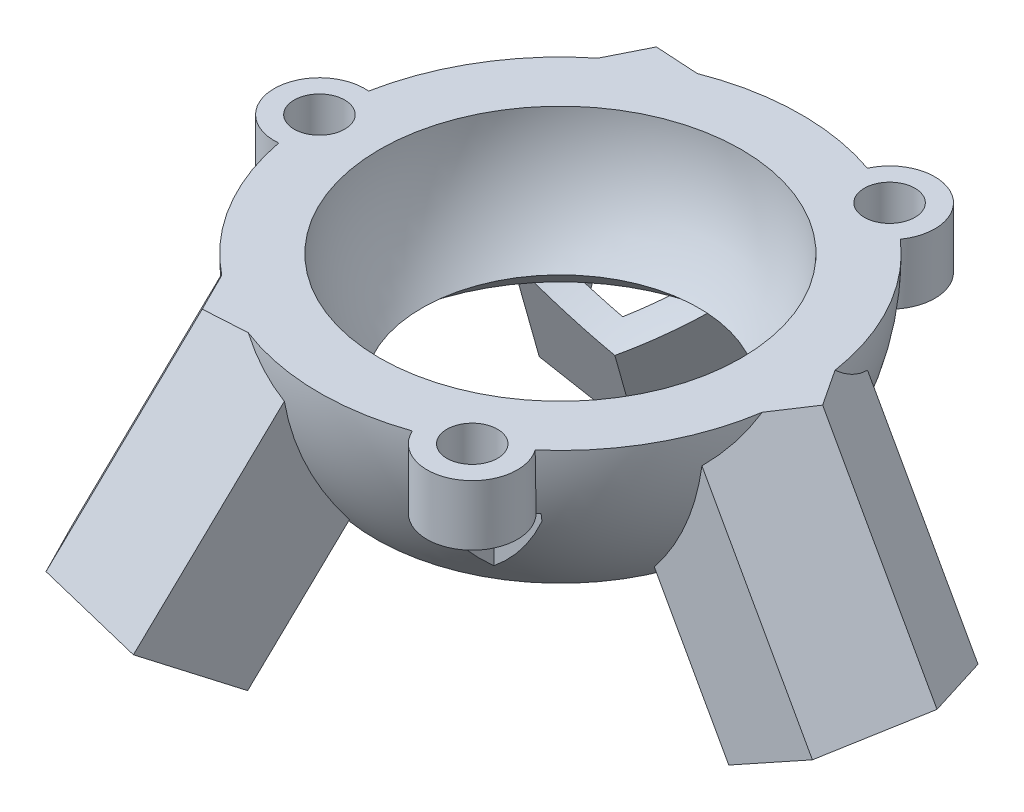
SolidWorks part; units mm, degrees
ref_plane "Ön Düzlem" through (0, 0, 0) normal (0, 0, 1) x (1, 0, 0)
ref_plane "Üst Düzlem" through (0, 0, 0) normal (0, 1, 0) x (1, 0, 0)
ref_plane "Sağ Düzlem" through (0, 0, 0) normal (1, 0, 0) x (0, 0, -1)
sketch "Çizim3" plane through (0, 0, 0) normal (0, 0, 1) x (1, 0, 0)
  line L0 (0, 24.312) -> (0, -34.2324) construction
  line L2 (-11.4907, -9.6418) -> (-15.3209, -12.8558)
  line L3 (-20, 0) -> (-15, 0)
  arc A0 (-15, 0) -> (-11.4907, -9.6418) centre (0, 0) ccw
  arc A1 (-20, 0) -> (-15.3209, -12.8558) centre (0, 0) ccw
  point P9 (0, 0)
  dimension "D1" = 30
  dimension "D2" = 5
revolve "Döndür1" add sketch "Çizim3" angle 360 about L0
sketch "Çizim4" plane through (0, 0, 0) normal (0, 1, 0) x (1, 0, 0)
  line L0 (0, 0) -> (-53.8435, 0) construction
  line L1 (0, 0) -> (20, 34.641) construction
  line L2 (0, 0) -> (20, -34.641) construction
  line L3 (10, 17.3205) -> (-20, 0) construction
  line L4 (-20, 0) -> (10, -17.3205) construction
  line L5 (10, -17.3205) -> (10, 17.3205) construction
  circle A0 centre (10, 17.3205) radius 1.75
  circle A1 centre (10, -17.3205) radius 1.75
  circle A2 centre (-20, 0) radius 1.75
  circle A3 centre (0, 0) radius 20 construction
  circle A4 centre (10, 17.3205) radius 3.75
  circle A5 centre (-20, 0) radius 3.75
  circle A6 centre (10, -17.3205) radius 3.75
  dimension "D3" = 3.5
  dimension "D4" = 2
  dimension "D1" = 120
  dimension "D2" = 120
extrude "Yükseklik-Ekstrüzyon1" add sketch "Çizim4" against normal blind 5
sketch "Çizim5" plane through (0, 0, 0) normal (0, 1, 0) x (1, 0, 0)
  circle A0 centre (10, 17.3205) radius 2.1
  circle A1 centre (-20, 0) radius 2.1
  arc A2 (-19.9234, 1.7483) -> (-19.9234, -1.7483) centre (0, 0) ccw construction
  circle A3 centre (10, -17.3205) radius 2.1
  arc A4 (8.4476, -18.1284) -> (11.4758, -16.38) centre (0, 0) ccw construction
  dimension "D1" = 4.2
extrude "Kes-Ekstrüzyon1" cut sketch "Çizim5" against normal blind 24
ref_plane "Düzlem1" through (0, -41.1703, 0) normal (0, 1, 0) x (1, 0, 0)
sketch "Çizim6" plane through (0, -41.1703, 0) normal (0, 1, 0) x (1, 0, 0)
  line L0 (0, 0) -> (10.7692, 17.7646) construction
  line L1 (0, 0) -> (-20, 0) construction
  line L2 (0, 0) -> (10.7692, -17.7646) construction
  line L4 (-16, 0) -> (-18, 3.4641)
  line L5 (-18, 3.4641) -> (-22, 3.4641)
  line L6 (-22, 3.4641) -> (-24, 0)
  line L7 (-24, 0) -> (-22, -3.4641)
  line L8 (-22, -3.4641) -> (-18, -3.4641)
  line L9 (-18, -3.4641) -> (-16, 0)
  line L10 (8.7692, 14.3005) -> (12.7692, 14.3005)
  line L11 (12.7692, 14.3005) -> (14.7692, 17.7646)
  line L12 (14.7692, 17.7646) -> (12.7692, 21.2287)
  line L13 (12.7692, 21.2287) -> (8.7692, 21.2287)
  line L14 (8.7692, 21.2287) -> (6.7692, 17.7646)
  line L15 (6.7692, 17.7646) -> (8.7692, 14.3005)
  line L16 (8.7692, -14.3005) -> (6.7692, -17.7646)
  line L17 (6.7692, -17.7646) -> (8.7692, -21.2287)
  line L18 (8.7692, -21.2287) -> (12.7692, -21.2287)
  line L19 (12.7692, -21.2287) -> (14.7692, -17.7646)
  line L20 (14.7692, -17.7646) -> (12.7692, -14.3005)
  line L21 (12.7692, -14.3005) -> (8.7692, -14.3005)
  circle A0 centre (-20, 0) radius 3.4641 construction
  circle A1 centre (10.7692, 17.7646) radius 3.4641 construction
  circle A2 centre (10.7692, -17.7646) radius 3.4641 construction
  dimension "D1" = 8
extrude "Kes-Ekstrüzyon2" cut sketch "Çizim6" along normal up to surface (36.1703 mm away) up to face at (10.5217, -5, 18.2242)
sketch "Çizim7" plane through (0, 0, 0) normal (0, 1, 0) x (1, 0, 0)
  line L0 (0, 0) -> (-10, -17.3205) construction
  line L1 (0, 0) -> (20, 0) construction
  line L2 (0, 0) -> (-10, 17.3205) construction
  arc A0 (-19.6484, -3.7335) -> (6.5909, -18.8828) centre (0, 0) ccw construction
  arc A1 (13.0575, -15.1493) -> (13.0575, 15.1493) centre (0, 0) ccw construction
  arc A2 (6.5909, 18.8828) -> (-19.6484, 3.7335) centre (0, 0) ccw construction
sketch "Çizim8" plane through (0, 0, 0) normal (0, 0, 1) x (1, 0, 0)
  line L0 (0, 67.9516) -> (0, -85.0049) construction
sketch3d "3B Çizim2"
  line L0 (0, 22.8931, 0) -> (26.7388, -25.3451, 0) construction
  line L3 (0, 67.9516, 0) -> (0, -85.0049, 0) construction
  dimension "D1" = 29
ref_plane "Düzlem2" through (26.7388, -25.3451, 0) normal (0.4848, -0.8746, 0) x (-0.8746, -0.4848, 0)
sketch "Çizim9" plane through (26.7388, -25.3451, 0) normal (0.4848, -0.8746, 0) x (-0.8746, -0.4848, 0)
  line L0 (3.9672, 6.8714) -> (-3.9672, 6.8714)
  line L1 (5.625, 0) -> (2.8125, 4.8714)
  line L2 (2.8125, 4.8714) -> (-2.8125, 4.8714)
  line L3 (-2.8125, 4.8714) -> (-5.625, 0)
  line L4 (-5.625, 0) -> (-2.8125, -4.8714)
  line L5 (-2.8125, -4.8714) -> (2.8125, -4.8714)
  line L6 (2.8125, -4.8714) -> (5.625, 0)
  line L7 (-3.9672, 6.8714) -> (-7.9344, 0)
  line L8 (-7.9344, 0) -> (-3.9672, -6.8714)
  line L9 (-3.9672, -6.8714) -> (3.9672, -6.8714)
  line L10 (3.9672, -6.8714) -> (7.9344, 0)
  line L11 (7.9344, 0) -> (3.9672, 6.8714)
  circle A0 centre (0, 0) radius 4.8714 construction
  dimension "D1" = 11.25
  dimension "D2" = 2
extrude "Yükseklik-Ekstrüzyon2" add sketch "Çizim9" against normal up to surface (12.7546 mm away) from offset 5 offset against normal yes
pattern_circular "Dairesel Kaplama1" count 3 every 120 about axis through (0, 0, 0) along (0, 1, 0) of "Yükseklik-Ekstrüzyon2"
sketch "Çizim10" plane through (0, 0, 0) normal (0, 0, 1) x (1, 0, 0)
  line L1 (-25.4864, 0) -> (35.7825, 0)
  line L2 (-25.4864, 0) -> (-25.4864, 17.8912)
  line L3 (-25.4864, 17.8912) -> (35.7825, 17.8912)
  line L4 (35.7825, 0) -> (35.7825, 17.8912)
extrude "Kes-Ekstrüzyon3" cut sketch "Çizim10" against normal blind 39 and the other way blind 45
